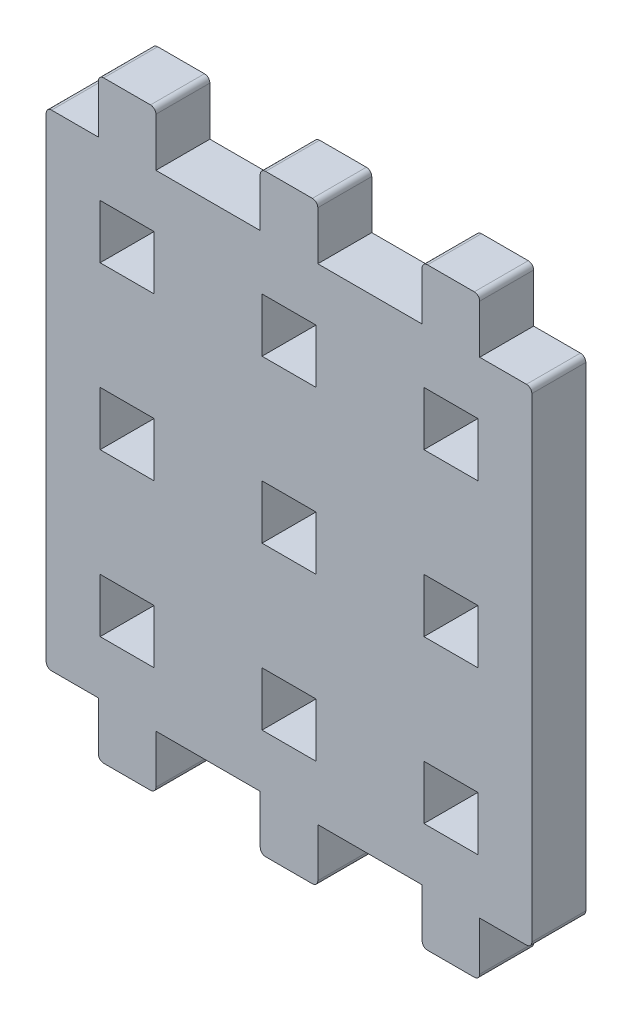
SolidWorks part; units mm, degrees
ref_plane "Alzado" through (0, 0, 0) normal (0, 0, 1) x (1, 0, 0)
ref_plane "Planta" through (0, 0, 0) normal (0, 1, 0) x (1, 0, 0)
ref_plane "Vista lateral" through (0, 0, 0) normal (1, 0, 0) x (0, 0, -1)
sketch "Model" plane through (0, 0, 0) normal (0, 0, 1) x (1, 0, 0)
  line L0 (11.9655, 295.0767) -> (11.9655, 292.0767)
  line L1 (14.9655, 295.0767) -> (11.9655, 295.0767)
  line L2 (14.9655, 292.0767) -> (14.9655, 295.0767)
  line L3 (11.9655, 292.0767) -> (14.9655, 292.0767)
  line L4 (20.9655, 295.0767) -> (20.9655, 292.0767)
  line L5 (23.9655, 295.0767) -> (20.9655, 295.0767)
  line L6 (23.9655, 292.0767) -> (23.9655, 295.0767)
  line L7 (20.9655, 292.0767) -> (23.9655, 292.0767)
  line L8 (29.9655, 295.0767) -> (29.9655, 292.0767)
  line L9 (32.9655, 295.0767) -> (29.9655, 295.0767)
  line L10 (32.9655, 292.0767) -> (32.9655, 295.0767)
  line L11 (29.9655, 292.0767) -> (32.9655, 292.0767)
  line L12 (11.9655, 277.0767) -> (11.9655, 274.0767)
  line L13 (14.9655, 277.0767) -> (11.9655, 277.0767)
  line L14 (14.9655, 274.0767) -> (14.9655, 277.0767)
  line L15 (11.9655, 274.0767) -> (14.9655, 274.0767)
  line L16 (20.9655, 277.0767) -> (20.9655, 274.0767)
  line L17 (23.9655, 277.0767) -> (20.9655, 277.0767)
  line L18 (23.9655, 274.0767) -> (23.9655, 277.0767)
  line L19 (20.9655, 274.0767) -> (23.9655, 274.0767)
  line L20 (29.9655, 277.0767) -> (29.9655, 274.0767)
  line L21 (32.9655, 277.0767) -> (29.9655, 277.0767)
  line L22 (32.9655, 274.0767) -> (32.9655, 277.0767)
  line L23 (29.9655, 274.0767) -> (32.9655, 274.0767)
  line L24 (11.9655, 286.0767) -> (11.9655, 283.0767)
  line L25 (14.9655, 286.0767) -> (11.9655, 286.0767)
  line L26 (14.9655, 283.0767) -> (14.9655, 286.0767)
  line L27 (11.9655, 283.0767) -> (14.9655, 283.0767)
  line L28 (20.9655, 286.0767) -> (20.9655, 283.0767)
  line L29 (23.9655, 286.0767) -> (20.9655, 286.0767)
  line L30 (23.9655, 283.0767) -> (23.9655, 286.0767)
  line L31 (20.9655, 283.0767) -> (23.9655, 283.0767)
  line L32 (29.9655, 286.0767) -> (29.9655, 283.0767)
  line L33 (32.9655, 286.0767) -> (29.9655, 286.0767)
  line L34 (32.9655, 283.0767) -> (32.9655, 286.0767)
  line L35 (29.9655, 283.0767) -> (32.9655, 283.0767)
  line L36 (8.9655, 297.7767) -> (8.9655, 271.3767)
  line L37 (35.9655, 297.7767) -> (35.9655, 271.3767)
  line L38 (11.8655, 300.7767) -> (11.8655, 298.0767)
  line L39 (15.0655, 298.0767) -> (15.0655, 300.7767)
  line L40 (12.1655, 301.0767) -> (14.7655, 301.0767)
  line L41 (9.2655, 298.0767) -> (11.8655, 298.0767)
  line L42 (24.0655, 298.0767) -> (29.8655, 298.0767)
  line L43 (20.8655, 300.7767) -> (20.8655, 298.0767)
  line L44 (24.0655, 298.0767) -> (24.0655, 300.7767)
  line L45 (21.1655, 301.0767) -> (23.7655, 301.0767)
  line L46 (15.0655, 298.0767) -> (20.8655, 298.0767)
  line L47 (29.8655, 300.7767) -> (29.8655, 298.0767)
  line L48 (33.0655, 298.0767) -> (33.0655, 300.7767)
  line L49 (30.1655, 301.0767) -> (32.7655, 301.0767)
  line L50 (33.0655, 298.0767) -> (35.6655, 298.0767)
  line L51 (11.8655, 268.3767) -> (11.8655, 271.0767)
  line L52 (15.0655, 271.0767) -> (15.0655, 268.3767)
  line L53 (12.1655, 268.0767) -> (14.7655, 268.0767)
  line L54 (9.2655, 271.0767) -> (11.8655, 271.0767)
  line L55 (24.0655, 271.0767) -> (29.8655, 271.0767)
  line L56 (20.8655, 268.3767) -> (20.8655, 271.0767)
  line L57 (24.0655, 271.0767) -> (24.0655, 268.3767)
  line L58 (21.1655, 268.0767) -> (23.7655, 268.0767)
  line L59 (15.0655, 271.0767) -> (20.8655, 271.0767)
  line L60 (29.8655, 268.3767) -> (29.8655, 271.0767)
  line L61 (33.0655, 271.0767) -> (33.0655, 268.3767)
  line L62 (30.1655, 268.0767) -> (32.7655, 268.0767)
  line L63 (33.0655, 271.0767) -> (35.6655, 271.0767)
  arc A0 (12.1655, 301.0767) -> (11.8655, 300.7767) centre (12.1655, 300.7767) ccw
  arc A1 (15.0655, 300.7767) -> (14.7655, 301.0767) centre (14.7655, 300.7767) ccw
  arc A2 (9.2655, 298.0767) -> (8.9655, 297.7767) centre (9.2655, 297.7767) ccw
  arc A3 (21.1655, 301.0767) -> (20.8655, 300.7767) centre (21.1655, 300.7767) ccw
  arc A4 (24.0655, 300.7767) -> (23.7655, 301.0767) centre (23.7655, 300.7767) ccw
  arc A5 (35.9655, 297.7767) -> (35.6655, 298.0767) centre (35.6655, 297.7767) ccw
  arc A6 (30.1655, 301.0767) -> (29.8655, 300.7767) centre (30.1655, 300.7767) ccw
  arc A7 (33.0655, 300.7767) -> (32.7655, 301.0767) centre (32.7655, 300.7767) ccw
  arc A8 (11.8655, 268.3767) -> (12.1655, 268.0767) centre (12.1655, 268.3767) ccw
  arc A9 (14.7655, 268.0767) -> (15.0655, 268.3767) centre (14.7655, 268.3767) ccw
  arc A10 (8.9655, 271.3767) -> (9.2655, 271.0767) centre (9.2655, 271.3767) ccw
  arc A11 (20.8655, 268.3767) -> (21.1655, 268.0767) centre (21.1655, 268.3767) ccw
  arc A12 (23.7655, 268.0767) -> (24.0655, 268.3767) centre (23.7655, 268.3767) ccw
  arc A13 (35.6655, 271.0767) -> (35.9655, 271.3767) centre (35.6655, 271.3767) ccw
  arc A14 (29.8655, 268.3767) -> (30.1655, 268.0767) centre (30.1655, 268.3767) ccw
  arc A15 (32.7655, 268.0767) -> (33.0655, 268.3767) centre (32.7655, 268.3767) ccw
extrude "Saliente-Extruir1" add sketch "Model" along normal blind 3
